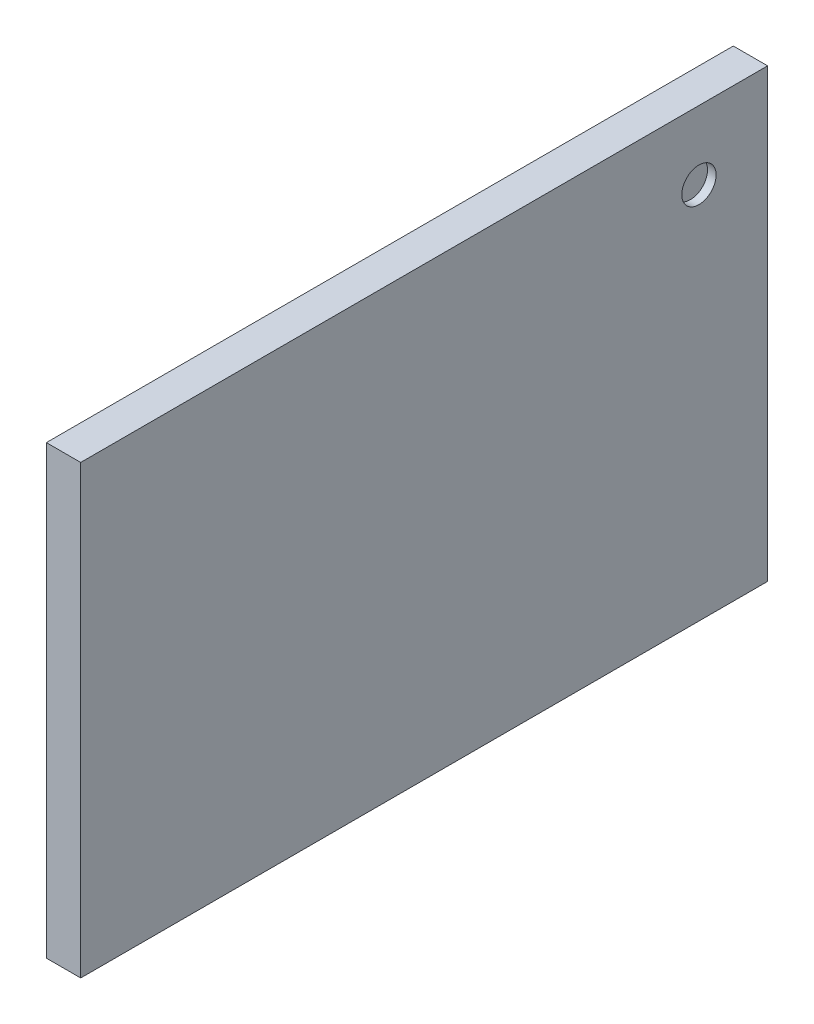
SolidWorks part; units mm, degrees
material "1060 Alloy"
ref_plane "Front Plane" through (0, 0, 0) normal (0, 0, 1) x (1, 0, 0)
ref_plane "Top Plane" through (0, 0, 0) normal (0, 1, 0) x (1, 0, 0)
ref_plane "Right Plane" through (0, 0, 0) normal (1, 0, 0) x (0, 0, -1)
sketch "Sketch1" plane through (0, 0, 0) normal (1, 0, 0) x (0, 0, -1)
  line L1 (-466.8184, 26.8007) -> (41.1816, 26.8007)
  line L2 (-466.8184, 26.8007) -> (-466.8184, -303.3993)
  line L3 (-466.8184, -303.3993) -> (41.1816, -303.3993)
  line L4 (41.1816, 26.8007) -> (41.1816, -303.3993)
  dimension "D1" = 508
  dimension "D2" = 330.2
extrude "Boss-Extrude1" add sketch "Sketch1" along normal blind 25.4
sketch "Sketch2" plane through (25.4, 0, 0) normal (1, 0, 0) x (0, 0, -1)
  line L0 (41.1816, 26.8007) -> (-466.8184, 26.8007) construction
  line L1 (41.1816, -303.3993) -> (41.1816, 26.8007) construction
  circle A0 centre (-9.6184, -23.9993) radius 12.7
  dimension "D1" = 25.4
  dimension "D2" = 50.8
  dimension "D3" = 50.8
extrude "Cut-Extrude1" cut sketch "Sketch2" against normal blind 6.35
